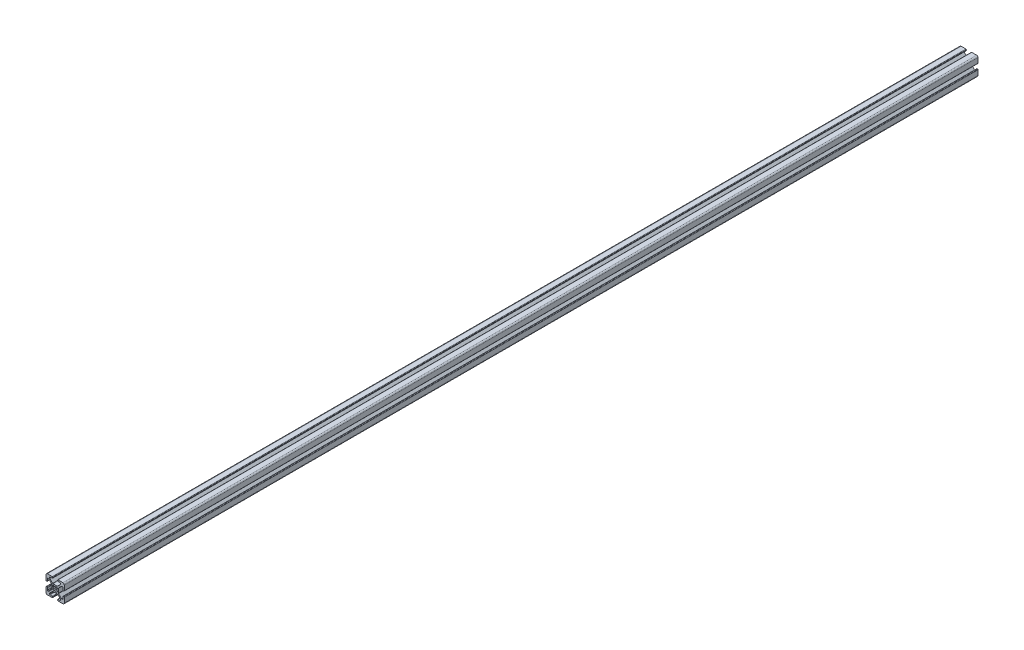
SolidWorks part; units mm, degrees
material "1060 Alloy"
ref_plane "Front Plane" through (0, 0, 0) normal (0, 0, 1) x (1, 0, 0)
ref_plane "Top Plane" through (0, 0, 0) normal (0, 1, 0) x (1, 0, 0)
ref_plane "Right Plane" through (0, 0, 0) normal (1, 0, 0) x (0, 0, -1)
sketch "Sketch2" plane through (0, 0, 0) normal (0, 0, 1) x (1, 0, 0)
  line L0 (-10, -3.138) -> (-10, -8.5)
  line L1 (-8.5, -10) -> (-3.138, -10)
  line L2 (-2.63, -9.492) -> (-2.63, -9.008)
  line L3 (-3.138, -8.5) -> (-5.487, -8.5)
  line L4 (-5.995, -7.992) -> (-5.995, -7.2662)
  line L5 (-5.8462, -6.907) -> (-2.743, -3.8038)
  line L6 (-2.3838, -3.655) -> (2.3841, -3.655)
  line L7 (2.7433, -3.8038) -> (5.8462, -6.9067)
  line L8 (5.995, -7.2659) -> (5.995, -7.992)
  line L9 (5.487, -8.5) -> (3.138, -8.5)
  line L10 (2.63, -9.008) -> (2.63, -9.492)
  line L11 (3.138, -10) -> (8.5, -10)
  line L12 (10, -8.5) -> (10, -3.138)
  line L13 (9.492, -2.63) -> (9.008, -2.63)
  line L14 (8.5, -3.138) -> (8.5, -5.487)
  line L15 (7.992, -5.995) -> (7.2662, -5.995)
  line L16 (6.907, -5.8462) -> (3.8038, -2.743)
  line L17 (3.655, -2.3838) -> (3.655, 2.3841)
  line L18 (3.8038, 2.7433) -> (6.9067, 5.8462)
  line L19 (7.2659, 5.995) -> (7.992, 5.995)
  line L20 (8.5, 5.487) -> (8.5, 3.138)
  line L21 (9.008, 2.63) -> (9.492, 2.63)
  line L22 (10, 3.138) -> (10, 8.5)
  line L23 (8.5, 10) -> (3.138, 10)
  line L24 (2.63, 9.492) -> (2.63, 9.008)
  line L25 (3.138, 8.5) -> (5.487, 8.5)
  line L26 (5.995, 7.992) -> (5.995, 7.2662)
  line L27 (5.8462, 6.907) -> (2.743, 3.8038)
  line L28 (2.3838, 3.655) -> (-2.3841, 3.655)
  line L29 (-2.7433, 3.8038) -> (-5.8462, 6.9067)
  line L30 (-5.995, 7.2659) -> (-5.995, 7.992)
  line L31 (-5.487, 8.5) -> (-3.138, 8.5)
  line L32 (-2.63, 9.008) -> (-2.63, 9.492)
  line L33 (-3.138, 10) -> (-8.5, 10)
  line L34 (-10, 8.5) -> (-10, 3.138)
  line L35 (-9.492, 2.63) -> (-9.008, 2.63)
  line L36 (-8.5, 3.138) -> (-8.5, 5.487)
  line L37 (-7.992, 5.995) -> (-7.2662, 5.995)
  line L38 (-6.907, 5.8462) -> (-3.8038, 2.743)
  line L39 (-3.655, 2.3838) -> (-3.655, -2.3841)
  line L40 (-3.8038, -2.7433) -> (-6.9067, -5.8462)
  line L41 (-7.2659, -5.995) -> (-7.992, -5.995)
  line L42 (-8.5, -5.487) -> (-8.5, -3.138)
  line L43 (-9.008, -2.63) -> (-9.492, -2.63)
  line L44 (-2.1245, 2.3045) -> (-2.3045, 2.1245)
  line L45 (2.3045, 2.1245) -> (2.1245, 2.3045)
  line L46 (2.1245, -2.3045) -> (2.3045, -2.1245)
  line L47 (-2.3045, -2.1245) -> (-2.1245, -2.3045)
  arc A0 (-10, -8.5) -> (-8.5, -10) centre (-8.5, -8.5) ccw
  arc A1 (-3.138, -10) -> (-2.63, -9.492) centre (-3.138, -9.492) ccw
  arc A2 (-2.63, -9.008) -> (-3.138, -8.5) centre (-3.138, -9.008) ccw
  arc A3 (-5.995, -7.992) -> (-5.487, -8.5) centre (-5.487, -7.992) ccw
  arc A4 (-5.8462, -6.907) -> (-5.995, -7.2662) centre (-5.487, -7.2662) ccw
  arc A5 (-2.3838, -3.655) -> (-2.743, -3.8038) centre (-2.3838, -4.163) ccw
  arc A6 (2.7433, -3.8038) -> (2.3841, -3.655) centre (2.3841, -4.163) ccw
  arc A7 (5.995, -7.2659) -> (5.8462, -6.9067) centre (5.487, -7.2659) ccw
  arc A8 (5.487, -8.5) -> (5.995, -7.992) centre (5.487, -7.992) ccw
  arc A9 (3.138, -8.5) -> (2.63, -9.008) centre (3.138, -9.008) ccw
  arc A10 (2.63, -9.492) -> (3.138, -10) centre (3.138, -9.492) ccw
  arc A11 (8.5, -10) -> (10, -8.5) centre (8.5, -8.5) ccw
  arc A12 (10, -3.138) -> (9.492, -2.63) centre (9.492, -3.138) ccw
  arc A13 (9.008, -2.63) -> (8.5, -3.138) centre (9.008, -3.138) ccw
  arc A14 (7.992, -5.995) -> (8.5, -5.487) centre (7.992, -5.487) ccw
  arc A15 (6.907, -5.8462) -> (7.2662, -5.995) centre (7.2662, -5.487) ccw
  arc A16 (3.655, -2.3838) -> (3.8038, -2.743) centre (4.163, -2.3838) ccw
  arc A17 (3.8038, 2.7433) -> (3.655, 2.3841) centre (4.163, 2.3841) ccw
  arc A18 (7.2659, 5.995) -> (6.9067, 5.8462) centre (7.2659, 5.487) ccw
  arc A19 (8.5, 5.487) -> (7.992, 5.995) centre (7.992, 5.487) ccw
  arc A20 (8.5, 3.138) -> (9.008, 2.63) centre (9.008, 3.138) ccw
  arc A21 (9.492, 2.63) -> (10, 3.138) centre (9.492, 3.138) ccw
  arc A22 (10, 8.5) -> (8.5, 10) centre (8.5, 8.5) ccw
  arc A23 (3.138, 10) -> (2.63, 9.492) centre (3.138, 9.492) ccw
  arc A24 (2.63, 9.008) -> (3.138, 8.5) centre (3.138, 9.008) ccw
  arc A25 (5.995, 7.992) -> (5.487, 8.5) centre (5.487, 7.992) ccw
  arc A26 (5.8462, 6.907) -> (5.995, 7.2662) centre (5.487, 7.2662) ccw
  arc A27 (2.3838, 3.655) -> (2.743, 3.8038) centre (2.3838, 4.163) ccw
  arc A28 (-2.7433, 3.8038) -> (-2.3841, 3.655) centre (-2.3841, 4.163) ccw
  arc A29 (-5.995, 7.2659) -> (-5.8462, 6.9067) centre (-5.487, 7.2659) ccw
  arc A30 (-5.487, 8.5) -> (-5.995, 7.992) centre (-5.487, 7.992) ccw
  arc A31 (-3.138, 8.5) -> (-2.63, 9.008) centre (-3.138, 9.008) ccw
  arc A32 (-2.63, 9.492) -> (-3.138, 10) centre (-3.138, 9.492) ccw
  arc A33 (-8.5, 10) -> (-10, 8.5) centre (-8.5, 8.5) ccw
  arc A34 (-10, 3.138) -> (-9.492, 2.63) centre (-9.492, 3.138) ccw
  arc A35 (-9.008, 2.63) -> (-8.5, 3.138) centre (-9.008, 3.138) ccw
  arc A36 (-7.992, 5.995) -> (-8.5, 5.487) centre (-7.992, 5.487) ccw
  arc A37 (-6.907, 5.8462) -> (-7.2662, 5.995) centre (-7.2662, 5.487) ccw
  arc A38 (-3.655, 2.3838) -> (-3.8038, 2.743) centre (-4.163, 2.3838) ccw
  arc A39 (-3.8038, -2.7433) -> (-3.655, -2.3841) centre (-4.163, -2.3841) ccw
  arc A40 (-7.2659, -5.995) -> (-6.9067, -5.8462) centre (-7.2659, -5.487) ccw
  arc A41 (-8.5, -5.487) -> (-7.992, -5.995) centre (-7.992, -5.487) ccw
  arc A42 (-8.5, -3.138) -> (-9.008, -2.63) centre (-9.008, -3.138) ccw
  arc A43 (-9.492, -2.63) -> (-10, -3.138) centre (-9.492, -3.138) ccw
  arc A44 (-1.9358, 0.8037) -> (-1.9358, -0.8037) centre (0, 0) ccw
  arc A45 (-2.3045, 2.1245) -> (-1.9358, 0.8037) centre (-1.748, 1.568) ccw
  arc A46 (-0.8037, 1.9358) -> (-2.1245, 2.3045) centre (-1.568, 1.748) ccw
  arc A47 (0.8037, 1.9358) -> (-0.8037, 1.9358) centre (0, 0) ccw
  arc A48 (2.1245, 2.3045) -> (0.8037, 1.9358) centre (1.568, 1.748) ccw
  arc A49 (1.9358, 0.8037) -> (2.3045, 2.1245) centre (1.748, 1.568) ccw
  arc A50 (1.9358, -0.8037) -> (1.9358, 0.8037) centre (0, 0) ccw
  arc A51 (2.3045, -2.1245) -> (1.9358, -0.8037) centre (1.748, -1.568) ccw
  arc A52 (0.8037, -1.9358) -> (2.1245, -2.3045) centre (1.568, -1.748) ccw
  arc A53 (-0.8037, -1.9358) -> (0.8037, -1.9358) centre (0, 0) ccw
  arc A54 (-2.1245, -2.3045) -> (-0.8037, -1.9358) centre (-1.568, -1.748) ccw
  arc A55 (-1.9358, -0.8037) -> (-2.3045, -2.1245) centre (-1.748, -1.568) ccw
extrude "Boss-Extrude1" add sketch "Sketch2" against normal blind 1000
